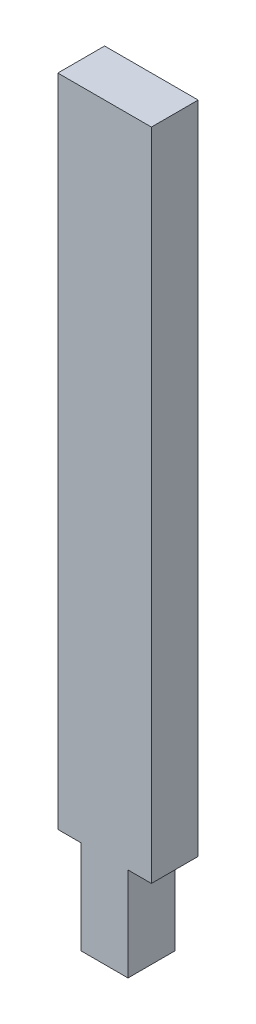
SolidWorks part; units mm, degrees
ref_plane "Plan de face" through (0, 0, 0) normal (0, 0, 1) x (1, 0, 0)
ref_plane "Plan de dessus" through (0, 0, 0) normal (0, 1, 0) x (1, 0, 0)
ref_plane "Plan de droite" through (0, 0, 0) normal (1, 0, 0) x (0, 0, -1)
sketch "Esquisse1" plane through (0, 0, 0) normal (0, 0, 1) x (1, 0, 0)
  line L0 (7.5, 0) -> (10, 0)
  line L1 (0, 0) -> (2.5, 0)
  line L2 (0, 0) -> (0, 70)
  line L3 (0, 70) -> (10, 70)
  line L4 (10, 0) -> (10, 70)
  line L6 (2.5, 0) -> (2.5, -10)
  line L7 (2.5, -10) -> (7.5, -10)
  line L8 (7.5, 0) -> (7.5, -10)
  dimension "D1" = 70
  dimension "D2" = 10
  dimension "D3" = 5
  dimension "D4" = 10
  dimension "D5" = 2.5
extrude "Boss.-Extru.1" add sketch "Esquisse1" along normal blind 5
